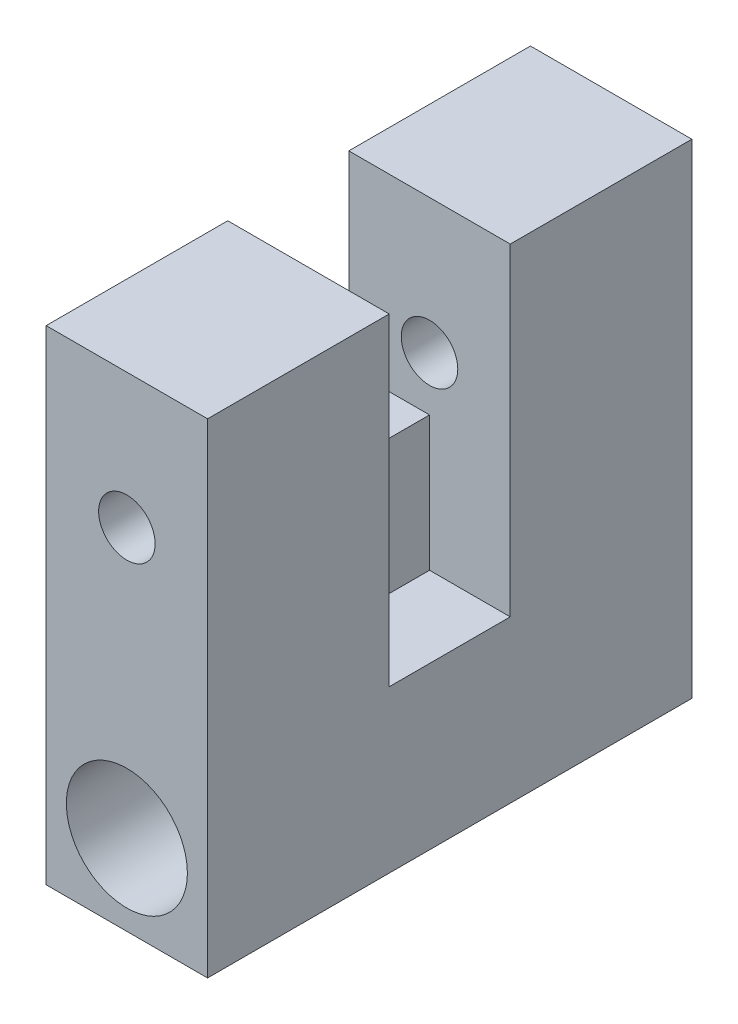
SolidWorks part; units mm, degrees
ref_plane "Front Plane" through (0, 0, 0) normal (0, 0, 1) x (1, 0, 0)
ref_plane "Top Plane" through (0, 0, 0) normal (0, 1, 0) x (1, 0, 0)
ref_plane "Right Plane" through (0, 0, 0) normal (1, 0, 0) x (0, 0, -1)
sketch "Sketch2" plane through (0, 0, 0) normal (0, 0, 1) x (1, 0, 0)
  line L1 (-3, -9) -> (3, -9)
  line L2 (-3, -9) -> (-3, 9)
  line L3 (-3, 9) -> (3, 9)
  line L4 (3, -9) -> (3, 9)
  line L5 (-3, -9) -> (3, 9) construction
  line L6 (-3, 9) -> (3, -9) construction
  point P0 (0, 0)
  dimension "D1" = 6
  dimension "D2" = 18
extrude "Boss-Extrude1" add sketch "Sketch2" along normal blind 18
sketch "Sketch3" plane through (0, 0, 18) normal (0, 0, 1) x (1, 0, 0)
  line L0 (-3, -9) -> (3, -9) construction
  circle A0 centre (0, -6) radius 2.25
  dimension "D1" = 3
extrude "Cut-Extrude1" cut sketch "Sketch3" against normal through all
sketch "Sketch4" plane through (3, 0, 0) normal (1, 0, 0) x (0, 0, -1)
  line L0 (-18, 9) -> (0, 9) construction
  line L1 (-11.25, -3) -> (-6.75, -3)
  line L2 (-11.25, -3) -> (-11.25, 9)
  line L3 (-11.25, 9) -> (-6.75, 9)
  line L4 (-6.75, -3) -> (-6.75, 9)
  line L5 (-11.25, -3) -> (-6.75, 9) construction
  line L6 (-11.25, 9) -> (-6.75, -3) construction
  line L7 (0, -9) -> (0, 9) construction
  point P0 (-9, 3)
  dimension "D1" = 4.5
  dimension "D2" = 6.75
  dimension "D3" = 12
extrude "Cut-Extrude2" cut sketch "Sketch4" against normal blind 3
sketch "Sketch5" plane through (0, 0, 18) normal (0, 0, 1) x (1, 0, 0)
  line L0 (3, 9) -> (-3, 9) construction
  circle A0 centre (0, 4) radius 1.05
  dimension "D1" = 5
extrude "Cut-Extrude3" cut sketch "Sketch5" against normal through all
sketch "Sketch8" plane through (3, 0, 0) normal (1, 0, 0) x (0, 0, -1)
  line L0 (-11.25, 9) -> (-11.25, -3) construction
  line L1 (-6.75, 9) -> (-11.25, 9)
  line L2 (-6.75, 9) -> (-6.75, 2)
  line L3 (-6.75, 2) -> (-11.25, 2)
  line L4 (-11.25, 9) -> (-11.25, 2)
  dimension "D1" = 7
extrude "Cut-Extrude6" cut sketch "Sketch8" against normal blind 10
